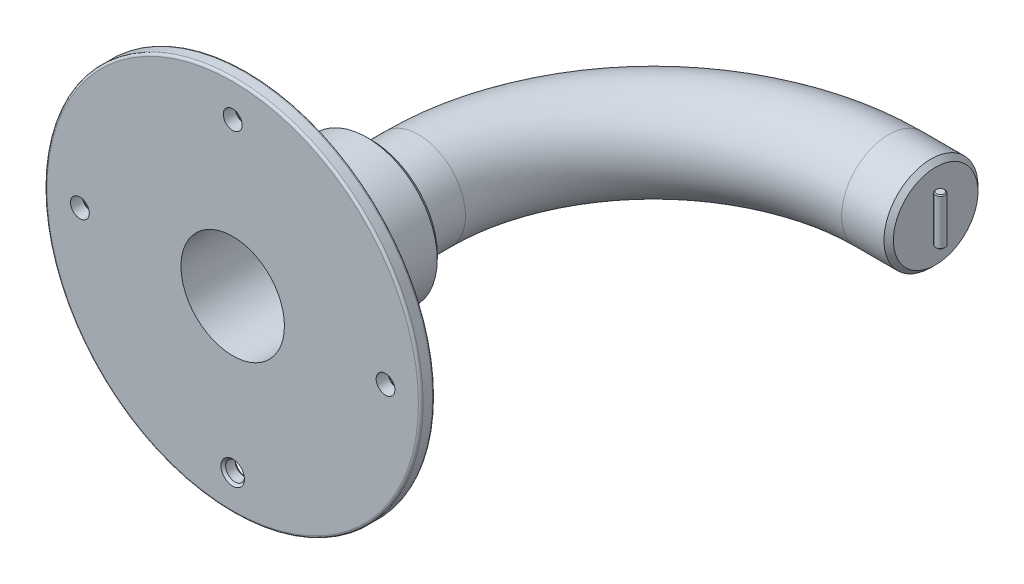
SolidWorks part; units mm, degrees
material "ABS"
ref_plane "Front Plane" through (0, 0, 0) normal (0, 0, 1) x (1, 0, 0)
ref_plane "Top Plane" through (0, 0, 0) normal (0, 1, 0) x (1, 0, 0)
ref_plane "Right Plane" through (0, 0, 0) normal (1, 0, 0) x (0, 0, -1)
sketch "Sketch1" plane through (0, 0, 0) normal (0, 0, 1) x (1, 0, 0)
  circle A0 centre (0, 0) radius 15
  dimension "D1" = 30
extrude "Boss-Extrude1" add sketch "Sketch1" along normal blind 29.5
sketch "Sketch2" plane through (0, 0, 29.5) normal (0, 0, 1) x (1, 0, 0)
  circle A0 centre (0, 0) radius 40
  dimension "D1" = 80
extrude "Boss-Extrude2" add sketch "Sketch2" against normal blind 3
chamfer "Chamfer1" distance 1 angle 45 2 edges at (15, 0, 26.5) (15, 0, 0)
sketch "Sketch3" plane through (0, 0, 29.5) normal (0, 0, 1) x (1, 0, 0)
  circle A0 centre (0, 0) radius 11
  circle A1 centre (0, 0) radius 14 construction
  dimension "D1" = 3
extrude "Cut-Extrude1" cut sketch "Sketch3" against normal blind 26
fillet "Fillet1" radius 0.5 2 edges at (40, 0, 26.5) (40, 0, 29.5)
sketch "Sketch4" plane through (0, 0, 26.5) normal (0, 0, -1) x (-1, 0, 0)
  line L0 (0, 32.5) -> (0, 0) construction
  circle A0 centre (0, 32.5) radius 2
  dimension "D1" = 4
  dimension "D2" = 32.5
extrude "Cut-Extrude2" cut sketch "Sketch4" against normal blind 26
pattern_circular "CirPattern1" count 4 over 360 about axis through (0, 0, 0) along (0, 0, 1) of "Cut-Extrude2"
chamfer "Chamfer2" distance 0.5 angle 45 5 edges at (2, -32.5, 26.5) (2, -32.5, 29.5) (32.5, 2, 26.5) (-32.5, -2, 26.5) (-2, 32.5, 26.5)
sketch "Sketch5" plane through (0, 0, 0) normal (0, 1, 0) x (1, 0, 0)
  line L0 (0, 0) -> (0, 10)
  line L1 (50, 60) -> (60, 60)
  arc A0 (0, 10) -> (50, 60) centre (50, 10) cw
  dimension "D1" = 50
  dimension "D2" = 10
  dimension "D3" = 10
sketch "Sketch6" plane through (0, 0, 0) normal (0, 0, -1) x (-1, 0, 0)
  circle A0 centre (0, 0) radius 10
  dimension "D1" = 20
sweep "Sweep1" add profiles "Sketch6" path "Sketch5"
chamfer "Chamfer3" distance 1 angle 45 1 edges at (60, 0, -70)
ref_plane "Plane1" through (0, 0, 0) normal (0, -1, 0) x (1, 0, 0)
sketch "Sketch7" plane through (0, 0, 0) normal (0, -1, 0) x (1, 0, 0)
  line L0 (60, -69) -> (60, -51) construction
  line L1 (60, -60) -> (62.7888, -60) construction
  circle A0 centre (61, -60) radius 1
  point P4 (61, -60)
  point P7 (61, -60)
  point P8 (61, -59.649)
  dimension "D1" = 2
extrude "Boss-Extrude3" add sketch "Sketch7" along normal mid plane 10 separate body
chamfer "Chamfer4" distance 0.2 angle 45 2 edges at (61, 5, -61) (61, -5, -61)
